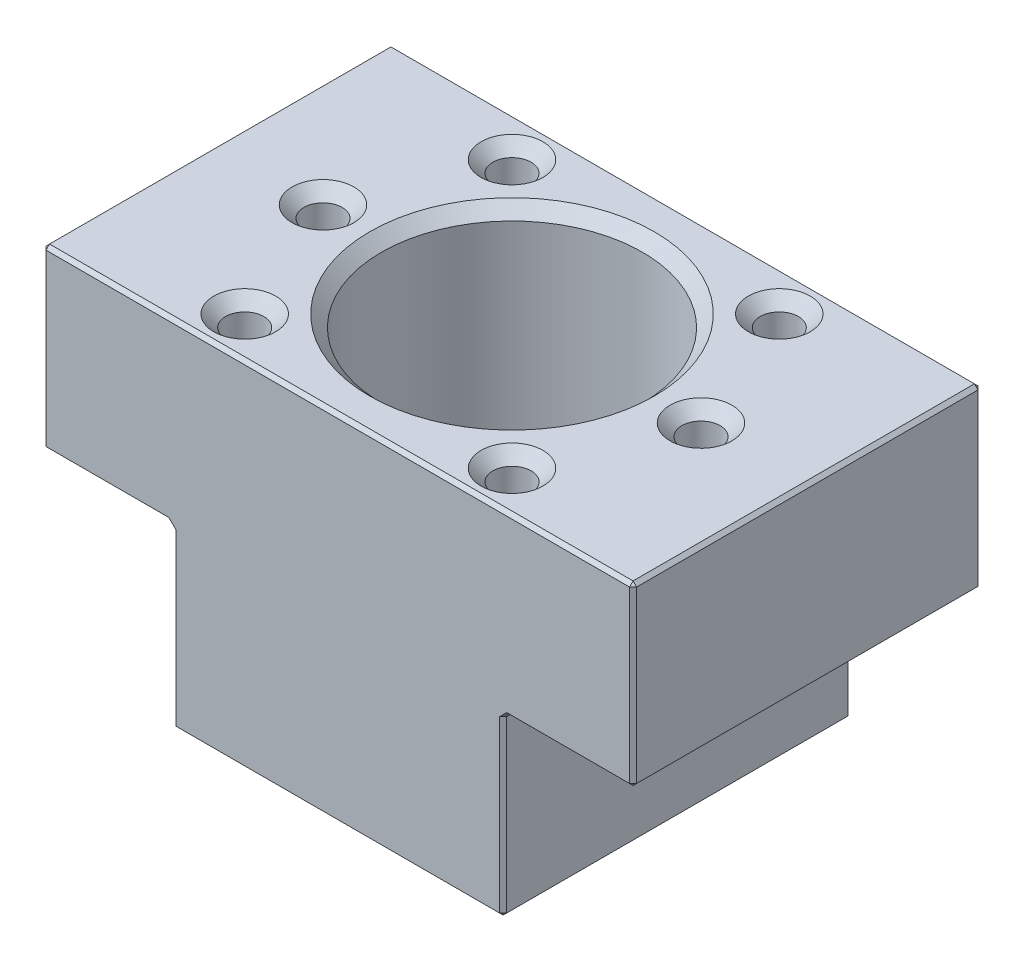
SolidWorks part; units mm, degrees
ref_plane "Front Plane" through (0, 0, 0) normal (0, 0, 1) x (1, 0, 0)
ref_plane "Top Plane" through (0, 0, 0) normal (0, 1, 0) x (1, 0, 0)
ref_plane "Right Plane" through (0, 0, 0) normal (1, 0, 0) x (0, 0, -1)
sketch "Sketch1" plane through (0, 0, 0) normal (0, 0, 1) x (1, 0, 0)
  line L0 (0, 67.4686) -> (0, 37.5523) construction
  line L1 (14, -15) -> (-14, -15)
  line L2 (-14, -15) -> (-14, 0)
  line L3 (-14, 0) -> (-25, 0)
  line L4 (-25, 0) -> (-25, 15)
  line L5 (-25, 15) -> (25, 15)
  line L6 (-14, 0) -> (0, 0) construction
  line L7 (14, -15) -> (14, 0)
  line L8 (14, 0) -> (25, 0)
  line L9 (25, 0) -> (25, 15)
  point P11 (0, -15)
  point P14 (0, 15)
  dimension "D1" = 50
  dimension "D2" = 28
  dimension "D3" = 15
extrude "Boss-Extrude1" add sketch "Sketch1" along normal mid plane 29.5
sketch "Sketch2" plane through (0, 15, 0) normal (0, 1, 0) x (1, 0, 0)
  circle A0 centre (0, 0) radius 11.05
  dimension "D1" = 22.1
extrude "Cut-Extrude1" cut sketch "Sketch2" against normal through all
sketch "Sketch4" plane through (0, 0, -14.75) normal (0, 0, -1) x (-1, 0, 0)
  line L0 (-17.5, 9) -> (17.5, 9) construction
  line L1 (0, 9) -> (0, 0) construction
  line L2 (0, 0) -> (0, -9) construction
  line L3 (-25, 15) -> (25, 15) construction
  line L4 (14, -15) -> (-14, -15) construction
  circle A0 centre (-17.5, 9) radius 2.115
  circle A1 centre (17.5, 9) radius 2.115
  circle A2 centre (0, -9) radius 2.115
  dimension "D1" = 4.23
  dimension "D2" = 6
  dimension "D3" = 35
  dimension "D4" = 6
extrude "Cut-Extrude2" cut sketch "Sketch4" against normal blind 12
sketch "Sketch5" plane through (0, 15, 0) normal (0, 1, 0) x (1, 0, 0)
  line L0 (0, 0) -> (16, 0) construction
  circle A0 centre (16, 0) radius 1.62
  circle A1 centre (11.3137, -11.3137) radius 1.62
  circle A2 centre (0, -16) radius 1.62 construction
  circle A3 centre (-11.3137, -11.3137) radius 1.62
  circle A4 centre (-16, 0) radius 1.62
  circle A5 centre (-11.3137, 11.3137) radius 1.62
  circle A6 centre (0, 16) radius 1.62 construction
  circle A7 centre (11.3137, 11.3137) radius 1.62
  point P20 (0, 0)
  dimension "D2" = 3.24
  dimension "D1" = 16
  dimension "D3" = 8
extrude "Cut-Extrude3" cut sketch "Sketch5" against normal blind 12
chamfer "Chamfer1" distance 1 angle 45 7 edges at (9.6937, 15, -11.3137) (-12.9337, 15, -11.3137) (-17.62, 15, 0) (-12.9337, 15, 11.3137) (9.6937, 15, 11.3137) (14.38, 15, 0) (-11.05, 15, 0)
chamfer "Chamfer2" distance 0.5 angle 45 3 edges at (-2.115, -9, -14.75) (-19.615, 9, -14.75) (15.385, 9, -14.75)
chamfer "Chamfer3" distance 0.3 angle 45 25 edges at (-11.05, -15, 0) (0, -15, 14.75) (0, -15, -14.75) (14, -15, 0) (14, -7.5, 14.75) (14, -7.5, -14.75) (14, 0, 0) (19.5, 0, 14.75) (19.5, 0, -14.75) (25, 0, 0) (25, 7.5, 14.75) (25, 15, 0) (25, 7.5, -14.75) (-14, -7.5, 14.75) (-14, -15, 0) (-14, -7.5, -14.75) (-25, 15, 0) (0, 15, 14.75) (-25, 7.5, 14.75) (-25, 0, 0) (-19.5, 0, 14.75) (-14, 0, 0) (-19.5, 0, -14.75) (-25, 7.5, -14.75) (0, 15, -14.75)
